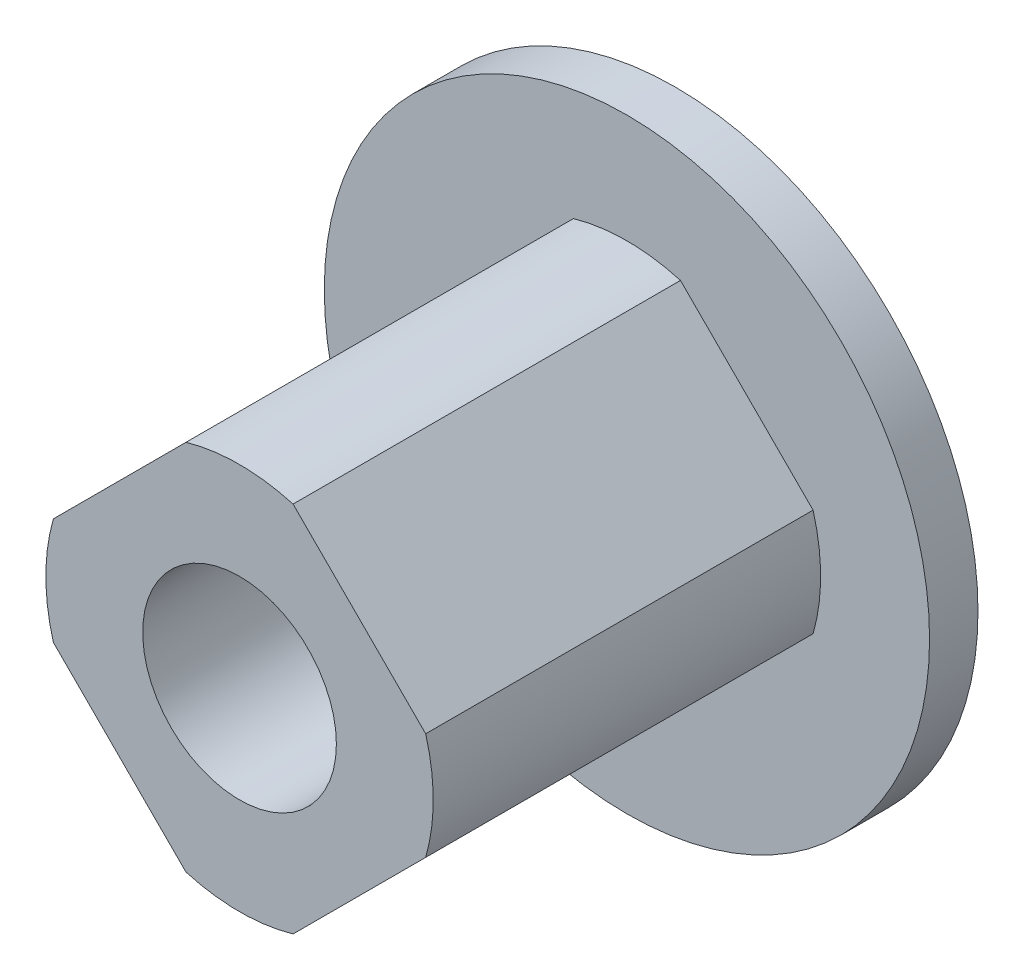
SolidWorks part; units mm, degrees
material "Plain Carbon Steel"
ref_plane "Front Plane" through (0, 0, 0) normal (0, 0, 1) x (1, 0, 0)
ref_plane "Top Plane" through (0, 0, 0) normal (0, 1, 0) x (1, 0, 0)
ref_plane "Right Plane" through (0, 0, 0) normal (1, 0, 0) x (0, 0, -1)
sketch "Sketch1" plane through (0, 0, 0) normal (0, 0, 1) x (1, 0, 0)
  circle A0 centre (0, 0) radius 12.7
  circle A1 centre (0, 0) radius 6.35
  dimension "D1" = 25.4
  dimension "D2" = 12.7
extrude "Boss-Extrude1" add sketch "Sketch1" along normal blind 3.175
sketch "Sketch2" plane through (0, 0, 3.175) normal (0, 0, 1) x (1, 0, 0)
  circle A0 centre (0, 0) radius 6.35 construction
  circle A1 centre (0, 0) radius 6.35
  circle A2 centre (0, 0) radius 19.8438
  dimension "D1" = 39.6875
extrude "Boss-Extrude2" add sketch "Sketch2" along normal blind 3.175
sketch "Sketch3" plane through (0, 0, 6.35) normal (0, 0, 1) x (1, 0, 0)
  circle A0 centre (0, 0) radius 6.35 construction
  circle A1 centre (0, 0) radius 12.7
  circle A2 centre (0, 0) radius 12.7
  circle A3 centre (0, 0) radius 6.35
  dimension "D1" = 0
extrude "Boss-Extrude3" add sketch "Sketch3" along normal blind 25.4
sketch "Sketch4" plane through (0, 0, 0) normal (0, 0, -1) x (-1, 0, 0)
  line L1 (-1.5875, 0) -> (1.5875, 0)
  line L2 (-1.5875, 0) -> (-1.5875, 9.525)
  line L3 (-1.5875, 9.525) -> (1.5875, 9.525)
  line L4 (1.5875, 0) -> (1.5875, 9.525)
  line L5 (-1.5875, 0) -> (1.5875, 9.525) construction
  line L6 (-1.5875, 9.525) -> (1.5875, 0) construction
  point P0 (0, 4.7625)
  dimension "D1" = 3.175
  dimension "D2" = 9.525
extrude "Cut-Extrude1" cut sketch "Sketch4" against normal blind 22.225
sketch "Sketch5" plane through (0, 0, 31.75) normal (0, 0, 1) x (1, 0, 0)
  line L0 (0, 0) -> (0, 15.7154) construction
  line L1 (0, 15.7154) -> (-15.7154, 0)
  line L2 (-15.7154, 0) -> (0, -15.7154)
  line L3 (0, -15.7154) -> (15.7154, 0)
  line L4 (15.7154, 0) -> (0, 15.7154)
  circle A0 centre (0, 0) radius 11.1125 construction
  circle A2 centre (0, 0) radius 23.837
  dimension "D1" = 22.225
extrude "Cut-Extrude2" cut sketch "Sketch5" against normal blind 25.4
